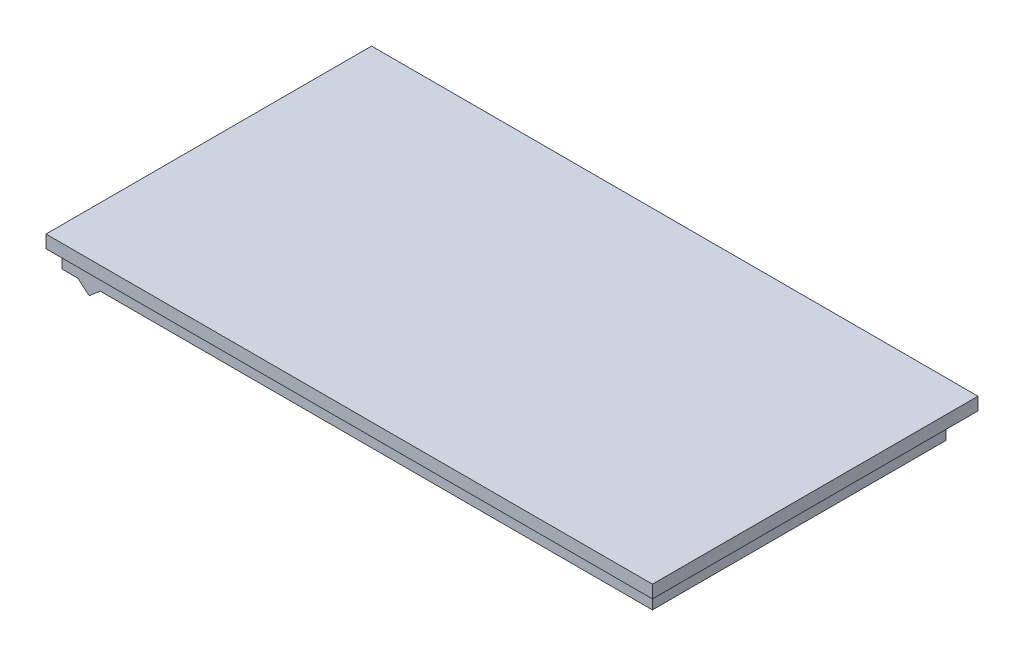
SolidWorks part; units mm, degrees
ref_plane "Plano frontal" through (0, 0, 0) normal (0, 0, 1) x (1, 0, 0)
ref_plane "Plano superior" through (0, 0, 0) normal (0, 1, 0) x (1, 0, 0)
ref_plane "Plano direito" through (0, 0, 0) normal (1, 0, 0) x (0, 0, -1)
sketch "Esboço1" plane through (0, 0, 0) normal (0, 1, 0) x (1, 0, 0)
  line L0 (0, 0) -> (0, 51)
  line L1 (0, 51) -> (95, 51)
  line L2 (95, 51) -> (95, 0)
  line L3 (95, 0) -> (0, 0)
  dimension "D1" = 95
  dimension "D2" = 51
extrude "Ressalto-extrusão1" add sketch "Esboço1" along normal blind 2
sketch "Esboço3" plane through (0, 0, 0) normal (0, -1, 0) x (-1, 0, 0)
  line L0 (-95, 0) -> (-95, 51) construction
  line L1 (-2.5, 6.5) -> (-92.5, 6.5)
  line L2 (-2.5, 6.5) -> (-2.5, 4.5)
  line L3 (-2.5, 4.5) -> (-92.5, 4.5)
  line L4 (-92.5, 6.5) -> (-92.5, 4.5)
  line L5 (0, 51) -> (0, 0) construction
  line L6 (0, 0) -> (-95, 0) construction
  dimension "D1" = 2.5
  dimension "D2" = 2
  dimension "D3" = 2.5
  dimension "D4" = 4.5
extrude "Ressalto-extrusão3" add sketch "Esboço3" along normal blind 2
sketch "Esboço5" plane through (0, 0, 0) normal (0, -1, 0) x (1, 0, 0)
  line L0 (92.5, -4.5) -> (2.5, -4.5) construction
  line L1 (2.5, -46.5) -> (92.5, -46.5)
  line L2 (2.5, -46.5) -> (2.5, -44.5)
  line L3 (2.5, -44.5) -> (92.5, -44.5)
  line L4 (92.5, -46.5) -> (92.5, -44.5)
  line L5 (95, -51) -> (0, -51) construction
  line L6 (95, 0) -> (95, -51) construction
  dimension "D1" = 2
  dimension "D2" = 4.5
  dimension "D3" = 2.5
extrude "Ressalto-extrusão4" add sketch "Esboço5" along normal blind 2
sketch "Esboço6" plane through (0, 0, 0) normal (0, -1, 0) x (1, 0, 0)
  line L0 (2.5, -46.5) -> (92.5, -46.5) construction
  line L1 (92.5, -4.5) -> (90.5, -4.5)
  line L2 (92.5, -4.5) -> (92.5, -46.5)
  line L3 (92.5, -46.5) -> (90.5, -46.5)
  line L4 (90.5, -4.5) -> (90.5, -46.5)
  dimension "D1" = 2
extrude "Ressalto-extrusão5" add sketch "Esboço6" along normal blind 4
sketch "Esboço7" plane through (0, -2, 0) normal (0, -1, 0) x (-1, 0, 0)
  line L0 (-95, 0) -> (-95, 51) construction
  line L1 (-2.5, 6.5) -> (-92.5, 6.5)
  line L2 (-2.5, 6.5) -> (-2.5, 2.5)
  line L3 (-2.5, 2.5) -> (-92.5, 2.5)
  line L4 (-92.5, 6.5) -> (-92.5, 2.5)
  line L5 (-2.5, 44.5) -> (-92.5, 44.5)
  line L6 (-2.5, 44.5) -> (-2.5, 48.5)
  line L7 (-2.5, 48.5) -> (-92.5, 48.5)
  line L8 (-92.5, 44.5) -> (-92.5, 48.5)
  dimension "D1" = 4
  dimension "D2" = 2.5
  dimension "D3" = 4
  dimension "D4" = 2.5
extrude "Ressalto-extrusão6" add sketch "Esboço7" along normal blind 2
sketch "Esboço8" plane through (0, 0, 0) normal (-1, 0, 0) x (0, 0, 1)
  line L0 (-51, 0) -> (0, 0) construction
  line L1 (-48.5, 0) -> (-2.5, 0)
  line L2 (-48.5, 0) -> (-48.5, -4)
  line L3 (-48.5, -4) -> (-2.5, -4)
  line L4 (-2.5, 0) -> (-2.5, -4)
  line L5 (0, 2) -> (0, 0) construction
  dimension "D1" = 4
  dimension "D2" = 2.5
  dimension "D3" = 2.5
extrude "Ressalto-extrusão7" add sketch "Esboço8" against normal blind 2.5
sketch "Esboço10" plane through (0, -4, 0) normal (0, -1, 0) x (1, 0, 0)
  line L0 (2.5, -6.5) -> (90.5, -6.5) construction
  line L1 (2.5, -2.5) -> (6, -2.5)
  line L2 (2.5, -2.5) -> (2.5, -6.5)
  line L3 (2.5, -6.5) -> (6, -6.5)
  line L4 (6, -2.5) -> (6, -6.5)
  line L5 (0, -48.5) -> (92.5, -48.5) construction
  line L6 (2.5, -44.5) -> (6, -44.5)
  line L7 (2.5, -44.5) -> (2.5, -48.5)
  line L8 (2.5, -48.5) -> (6, -48.5)
  line L9 (6, -44.5) -> (6, -48.5)
  dimension "D1" = 3.5
  dimension "D2" = 3.5
extrude "Ressalto-extrusão8" add sketch "Esboço10" along normal blind 1.5
sketch "Esboço12" plane through (0, 0, -2.5) normal (0, 0, 1) x (1, 0, 0)
  line L0 (2.5, -4) -> (4.25, -5.5)
  line L1 (6, -5.5) -> (2.5, -5.5) construction
  line L2 (4.25, -5.5) -> (2.5, -5.5)
  line L3 (2.5, -5.5) -> (2.5, -4)
extrude "Corte-extrusão1" cut sketch "Esboço12" against normal blind 52.5
sketch "Esboço13" plane through (0, 0, -2.5) normal (0, 0, 1) x (1, 0, 0)
  line L0 (4.25, -5.5) -> (6, -4)
  line L1 (6, -4) -> (6, -5.5)
  line L2 (6, -5.5) -> (4.25, -5.5)
extrude "Corte-extrusão2" cut sketch "Esboço13" against normal blind 62.5
